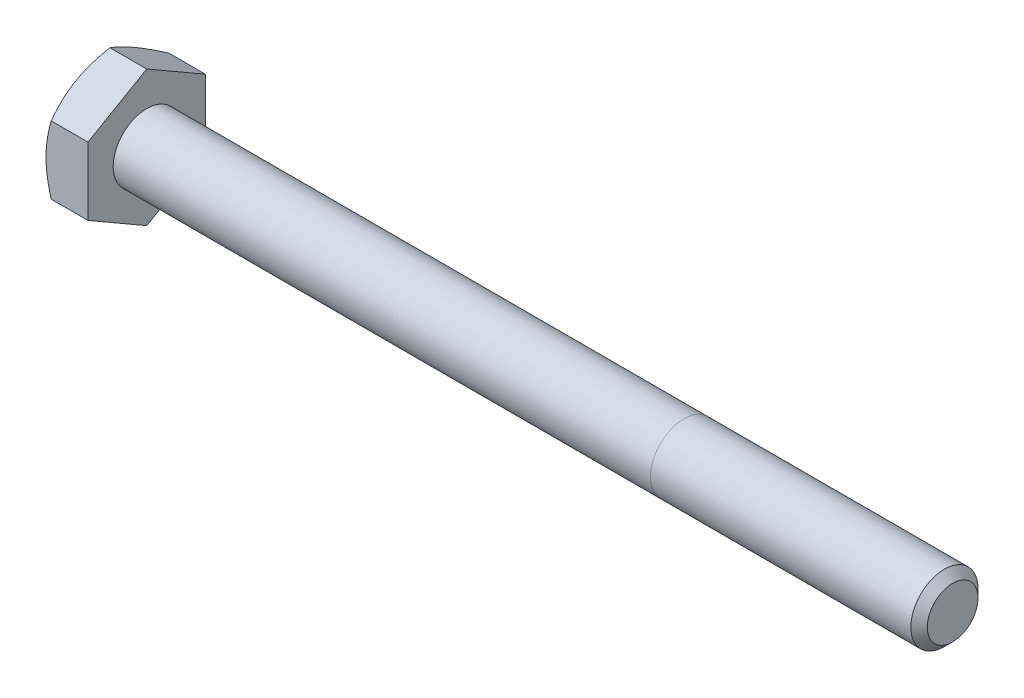
SolidWorks part; units mm, degrees
material "Alloy Steel"
ref_plane "Front Plane" through (0, 0, 0) normal (0, 0, 1) x (1, 0, 0)
ref_plane "Top Plane" through (0, 0, 0) normal (0, 1, 0) x (1, 0, 0)
ref_plane "Right Plane" through (0, 0, 0) normal (1, 0, 0) x (0, 0, -1)
sketch "Sketch1" plane through (0, 0, 0) normal (0, 0, 1) x (1, 0, 0)
  line L0 (-40.0844, 0) -> (40.0844, 0) construction
  line L1 (40.0844, 3.175) -> (40.0844, -3.175) construction
  line L2 (-36.1156, 5.5562) -> (-36.1156, -5.5562) construction
  line L3 (-40.0844, 5.5562) -> (-40.0844, -5.5562) construction
  point P9 (-36.1156, 0)
  point P10 (35.6394, -3.175)
  point P11 (14.6844, 0)
  dimension "D1" = 4.445
  dimension "Screw Dia" = 6.35
  dimension "Hex" = 11.1125
  dimension "Head Ht" = 3.9688
  dimension "Screw Lenght" = 76.2
  dimension "D2" = 25.4
ref_plane "Plane2" through (40.0844, 0, 0) normal (1, 0, 0) x (0, 0, -1)
sketch "Sketch5" plane through (40.0844, 0, 0) normal (1, 0, 0) x (0, 0, -1)
  circle A0 centre (0, 0) radius 3.175
extrude "Boss-Extrude3" add sketch "Sketch5" against normal up to vertex (76.2 mm away) up to point (-36.1156, 0, 0)
sketch "Sketch9" plane through (40.0844, 0, 0) normal (1, 0, 0) x (0, 0, -1)
  circle A1 centre (0, 0) radius 3.175
  circle A2 centre (0, 0) radius 3.175
  dimension "D1" = 0
curve "Helix/Spiral1" pitch 1.27 height 77.47 turns 61 parameters "Pitch"=1.27
chamfer "Chamfer1" distance 0.7772 angle 45 1 edges at (40.0844, 0, -3.175)
sketch "Sketch10" plane through (0, 0, 0) normal (0, 0, 1) x (1, 0, 0)
  line L0 (40.0844, 3.175) -> (40.5606, 2.3501)
  line L1 (40.5606, 2.3501) -> (40.7194, 2.3501)
  line L2 (40.7194, 2.3501) -> (41.1956, 3.175)
  line L3 (40.0844, 3.175) -> (41.1956, 3.175)
  line L4 (40.64, 3.175) -> (40.64, 2.3501) construction
  line L5 (40.3225, 2.7626) -> (40.9575, 2.7626) construction
  dimension "D1" = 60
  dimension "D2" = 0.1588
  dimension "D3" = 0.635
sketch "Sketch6" plane through (-36.1156, 0, 0) normal (-1, 0, 0) x (0, 0, 1)
  line L0 (0, 5.5562) -> (0, -5.5562) construction
  line L1 (5.5563, 3.2079) -> (0, 6.4158)
  line L2 (0, 6.4158) -> (-5.5562, 3.2079)
  line L3 (-5.5562, 3.2079) -> (-5.5562, -3.2079)
  line L4 (-5.5562, -3.2079) -> (0, -6.4158)
  line L5 (0, -6.4158) -> (5.5563, -3.2079)
  line L6 (5.5563, -3.2079) -> (5.5563, 3.2079)
  circle A0 centre (0, 0) radius 5.5563 construction
extrude "Boss-Extrude4" add sketch "Sketch6" along normal up to vertex (3.9688 mm away) up to point (-40.0844, -5.5562, 0)
sketch "Sketch7" plane through (-40.0844, 0, 0) normal (-1, 0, 0) x (0, 0, 1)
  circle A0 centre (0, 0) radius 5.5563 construction
  circle A1 centre (0, 0) radius 5.5563
sketch "Sketch8" plane through (-40.0844, 0, 0) normal (-1, 0, 0) x (0, 0, 1)
  circle A0 centre (0, 0) radius 5.5563 construction
  circle A1 centre (0, 0) radius 5.5563
extrude "Cut-Extrude3" cut sketch "Sketch8" against normal through all draft 60 flip side to cut
sketch "Sketch12" plane through (-40.0844, 0, 0) normal (-1, 0, 0) x (0, 0, 1)
  line L0 (0, 4.2783) -> (0, 2.3892) construction
  line L1 (0.1667, 4.2783) -> (0.1667, 2.3892)
  line L2 (-0.1667, 4.2783) -> (-0.1667, 2.3892)
  line L3 (0, 3.175) -> (0, -3.175) construction
  arc A0 (0.1667, 4.2783) -> (-0.1667, 4.2783) centre (0, 4.2783) ccw
  arc A1 (-0.1667, 2.3892) -> (0.1667, 2.3892) centre (0, 2.3892) ccw
  circle A3 centre (0, 0) radius 2.2225 construction
  circle A4 centre (0, 0) radius 4.445 construction
  point P2 (0, 3.3337)
  dimension "D1" = 4.445
  dimension "D3" = 8.89
  dimension "D2" = 0.3334
extrude "Cut-Extrude4" cut sketch "Sketch12" against normal blind 0.254
pattern_circular "CirPattern1" count 3 over 360 about axis through (0, 0, 0) along (1, 0, 0) of "Cut-Extrude4"
sketch "Sketch13" plane through (0, 0, 0) normal (0, 0, 1) x (1, 0, 0)
  line L0 (14.6844, 3.175) -> (14.6844, -3.175)
  line L2 (-36.1156, -3.175) -> (39.3071, -3.175) construction
  point P4 (14.6844, 0)
split line "Split Line1"
equation "\"D2@Sketch10\" = \"Pitch@Helix/Spiral1\"*.125"
equation "\"D3@Sketch10\" = \"Pitch@Helix/Spiral1\"*.5"
equation "\"D1@Chamfer1\" = \"Pitch@Helix/Spiral1\"*.612"
equation "\"D1@Sketch12\" = \"Hex@Sketch1\"*.4"
equation "\"D3@Sketch12\" = \"Hex@Sketch1\"*.8"
equation "\"D2@Sketch12\" = \"Hex@Sketch1\"*.03"
equation "\"D1@Sketch1\" = \"Pitch@Helix/Spiral1\"*3.5"
equation "\"D3@Helix/Spiral1\" = \"Screw Lenght@Sketch1\"+\"Pitch@Helix/Spiral1\""
